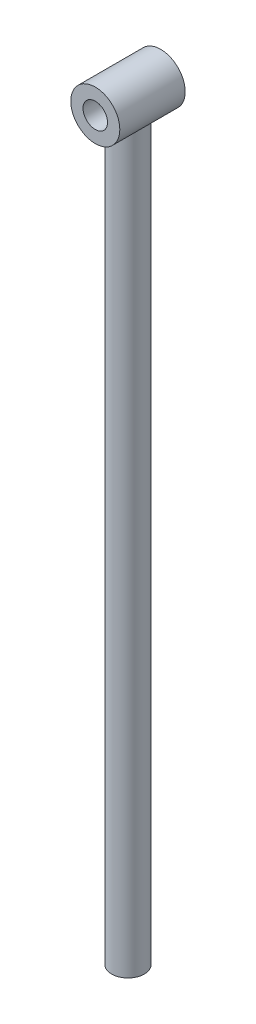
SolidWorks part; units mm, degrees
ref_plane "Front Plane" through (0, 0, 0) normal (0, 0, 1) x (1, 0, 0)
ref_plane "Top Plane" through (0, 0, 0) normal (0, 1, 0) x (1, 0, 0)
ref_plane "Right Plane" through (0, 0, 0) normal (1, 0, 0) x (0, 0, -1)
sketch "Sketch1" plane through (0, 0, 0) normal (0, 0, 1) x (1, 0, 0)
  circle A0 centre (0, 0) radius 15
  circle A1 centre (0, 0) radius 30
  dimension "D1" = 60
  dimension "D2" = 30
  dimension "D3" = 15
extrude "Boss-Extrude1" add sketch "Sketch1" along normal mid plane 80
ref_plane "Plane1" through (0, -920, 0) normal (0, 1, 0) x (1, 0, 0)
sketch "Sketch2" plane through (0, -920, 0) normal (0, 1, 0) x (1, 0, 0)
  circle A0 centre (0, 0) radius 20
  dimension "D1" = 40
extrude "Boss-Extrude2" add sketch "Sketch2" along normal up to surface (890 mm away)
